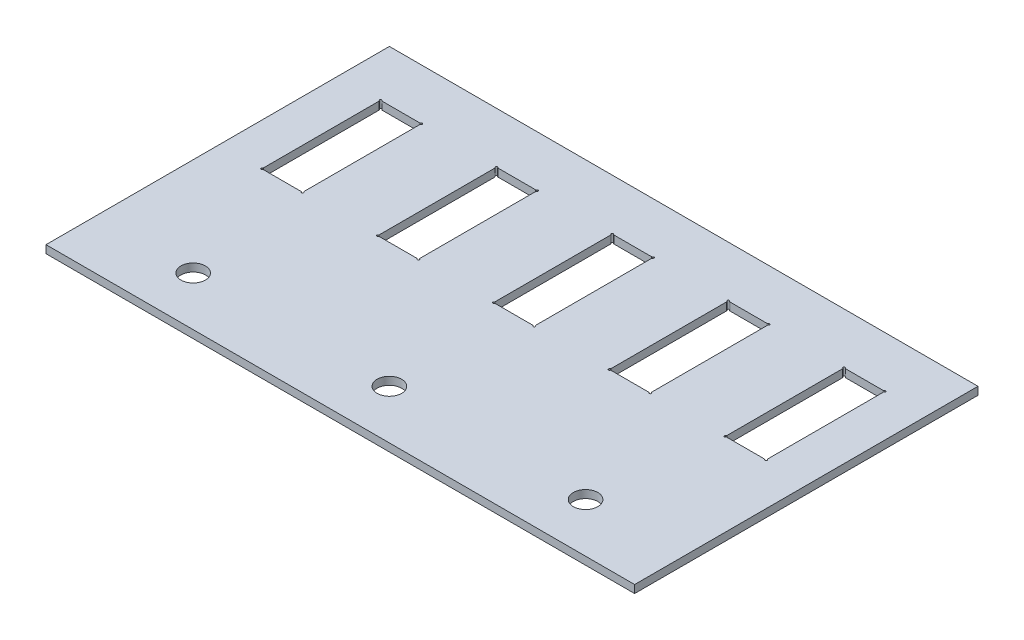
SolidWorks part; units mm, degrees
ref_plane "Front Plane" through (0, 0, 0) normal (0, 0, 1) x (1, 0, 0)
ref_plane "Top Plane" through (0, 0, 0) normal (0, 1, 0) x (1, 0, 0)
ref_plane "Right Plane" through (0, 0, 0) normal (1, 0, 0) x (0, 0, -1)
sketch "Sketch1" plane through (0, 0, 0) normal (0, 1, 0) x (1, 0, 0)
  line L0 (0, 12.7) -> (152.4, 12.7) construction
  line L1 (0, 0) -> (152.4, 0)
  line L2 (0, 0) -> (0, 88.9)
  line L3 (0, 88.9) -> (152.4, 88.9)
  line L4 (152.4, 0) -> (152.4, 88.9)
  line L5 (76.2, 88.9) -> (76.2, 0) construction
  line L6 (25.4, 0) -> (25.4, 88.9) construction
  circle A0 centre (76.2, 12.7) radius 3.175
  circle A1 centre (25.4, 12.7) radius 3.175
  circle A2 centre (127, 12.7) radius 3.175
  point P17 (18.0637, 12.7)
  dimension "D4" = 6.35
  dimension "D1" = 152.4
  dimension "D2" = 88.9
  dimension "D3" = 12.7
  dimension "D5" = 25.4
extrude "Boss-Extrude1" add sketch "Sketch1" along normal blind 2.032
sketch "Sketch2" plane through (0, 0, 0) normal (0, -1, 0) x (1, 0, 0)
  line L0 (81.4705, -75.259) -> (81.4705, -45.391)
  line L1 (71.3625, -75.692) -> (81.0375, -75.692)
  line L2 (111.4705, -75.259) -> (111.4705, -45.391)
  line L3 (101.3625, -75.692) -> (111.0375, -75.692)
  line L4 (152.4, -25.4) -> (0, -25.4) construction
  line L5 (152.4, 0) -> (152.4, -88.9) construction
  line L6 (0, -88.9) -> (0, 0) construction
  line L7 (0, 0) -> (152.4, 0) construction
  line L8 (81.0375, -44.958) -> (71.3625, -44.958)
  line L9 (111.0375, -44.958) -> (101.3625, -44.958)
  line L10 (100.9295, -45.391) -> (100.9295, -75.259)
  line L11 (70.9295, -45.391) -> (70.9295, -75.259)
  line L12 (106.2, -44.958) -> (106.2, -75.692) construction
  line L13 (111.4705, -60.325) -> (100.9295, -60.325) construction
  line L14 (141.4705, -75.259) -> (141.4705, -45.391)
  line L15 (131.3625, -75.692) -> (141.0375, -75.692)
  line L16 (141.0375, -44.958) -> (131.3625, -44.958)
  line L17 (130.9295, -45.391) -> (130.9295, -75.259)
  line L18 (136.2, -44.958) -> (136.2, -75.692) construction
  line L19 (141.4705, -60.325) -> (130.9295, -60.325) construction
  line L20 (81.4705, -75.259) -> (81.4705, -45.391)
  line L21 (71.3625, -75.692) -> (81.0375, -75.692)
  line L22 (81.0375, -44.958) -> (71.3625, -44.958)
  line L23 (70.9295, -45.391) -> (70.9295, -75.259)
  line L24 (76.2, -44.958) -> (76.2, -75.692) construction
  line L25 (81.4705, -60.325) -> (70.9295, -60.325) construction
  line L26 (111.4705, -75.259) -> (111.4705, -45.391)
  line L27 (101.3625, -75.692) -> (111.0375, -75.692)
  line L28 (111.0375, -44.958) -> (101.3625, -44.958)
  line L29 (100.9295, -45.391) -> (100.9295, -75.259)
  line L30 (106.2, -44.958) -> (106.2, -75.692) construction
  line L31 (111.4705, -60.325) -> (100.9295, -60.325) construction
  line L32 (51.4705, -75.259) -> (51.4705, -45.391)
  line L33 (41.3625, -75.692) -> (51.0375, -75.692)
  line L34 (51.0375, -44.958) -> (41.3625, -44.958)
  line L35 (40.9295, -45.391) -> (40.9295, -75.259)
  line L36 (46.2, -44.958) -> (46.2, -75.692) construction
  line L37 (51.4705, -60.325) -> (40.9295, -60.325) construction
  line L38 (81.4705, -75.259) -> (81.4705, -45.391)
  line L39 (71.3625, -75.692) -> (81.0375, -75.692)
  line L40 (81.0375, -44.958) -> (71.3625, -44.958)
  line L41 (70.9295, -45.391) -> (70.9295, -75.259)
  line L42 (76.2, -44.958) -> (76.2, -75.692) construction
  line L43 (81.4705, -60.325) -> (70.9295, -60.325) construction
  line L44 (51.4705, -75.259) -> (51.4705, -45.391)
  line L45 (41.3625, -75.692) -> (51.0375, -75.692)
  line L46 (51.0375, -44.958) -> (41.3625, -44.958)
  line L47 (40.9295, -45.391) -> (40.9295, -75.259)
  line L48 (46.2, -44.958) -> (46.2, -75.692) construction
  line L49 (51.4705, -60.325) -> (40.9295, -60.325) construction
  line L50 (21.4705, -75.259) -> (21.4705, -45.391)
  line L51 (11.3625, -75.692) -> (21.0375, -75.692)
  line L52 (21.0375, -44.958) -> (11.3625, -44.958)
  line L53 (10.9295, -45.391) -> (10.9295, -75.259)
  line L54 (16.2, -44.958) -> (16.2, -75.692) construction
  line L55 (21.4705, -60.325) -> (10.9295, -60.325) construction
  line L56 (81.4705, -75.259) -> (111.4705, -75.259) construction
  line L57 (81.4705, -75.259) -> (51.4705, -75.259) construction
  line L58 (152.4, -88.9) -> (152.4, -25.4) construction
  line L59 (152.4, -57.15) -> (0, -57.15) construction
  line L60 (76.2, -44.958) -> (76.2, -75.692) construction
  line L61 (81.4705, -60.325) -> (70.9295, -60.325) construction
  line L66 (81.4705, -44.958) -> (70.9295, -44.958)
  line L67 (81.4705, -75.692) -> (81.4705, -44.958)
  line L68 (70.9295, -75.692) -> (81.4705, -75.692)
  line L69 (70.9295, -44.958) -> (70.9295, -75.692)
  line L70 (81.4705, -44.958) -> (70.9295, -44.958) construction
  line L71 (81.4705, -75.692) -> (81.4705, -44.958) construction
  line L72 (70.9295, -75.692) -> (81.4705, -75.692) construction
  line L73 (70.9295, -44.958) -> (70.9295, -75.692) construction
  arc A0 (81.254, -75.817) -> (81.5955, -75.4755) centre (81.4705, -75.692) ccw
  arc A1 (70.8045, -75.4755) -> (71.146, -75.817) centre (70.9295, -75.692) ccw
  arc A2 (81.5955, -45.1745) -> (81.254, -44.833) centre (81.4705, -44.958) ccw
  arc A3 (71.146, -44.833) -> (70.8045, -45.1745) centre (70.9295, -44.958) ccw
  arc A4 (81.5955, -75.4755) -> (81.4705, -75.259) centre (81.7205, -75.259) cw
  arc A5 (81.254, -75.817) -> (81.0375, -75.692) centre (81.0375, -75.942) ccw
  arc A6 (71.146, -75.817) -> (71.3625, -75.692) centre (71.3625, -75.942) cw
  arc A7 (70.8045, -75.4755) -> (70.9295, -75.259) centre (70.6795, -75.259) ccw
  arc A8 (70.8045, -45.1745) -> (70.9295, -45.391) centre (70.6795, -45.391) cw
  arc A9 (71.146, -44.833) -> (71.3625, -44.958) centre (71.3625, -44.708) ccw
  arc A10 (81.5955, -45.1745) -> (81.4705, -45.391) centre (81.7205, -45.391) ccw
  arc A11 (81.254, -44.833) -> (81.0375, -44.958) centre (81.0375, -44.708) cw
  arc A12 (111.254, -75.817) -> (111.5955, -75.4755) centre (111.4705, -75.692) ccw
  arc A13 (100.8045, -75.4755) -> (101.146, -75.817) centre (100.9295, -75.692) ccw
  arc A14 (111.5955, -45.1745) -> (111.254, -44.833) centre (111.4705, -44.958) ccw
  arc A15 (101.146, -44.833) -> (100.8045, -45.1745) centre (100.9295, -44.958) ccw
  arc A16 (111.5955, -75.4755) -> (111.4705, -75.259) centre (111.7205, -75.259) cw
  arc A17 (111.254, -75.817) -> (111.0375, -75.692) centre (111.0375, -75.942) ccw
  arc A18 (101.146, -75.817) -> (101.3625, -75.692) centre (101.3625, -75.942) cw
  arc A19 (100.8045, -75.4755) -> (100.9295, -75.259) centre (100.6795, -75.259) ccw
  arc A20 (100.8045, -45.1745) -> (100.9295, -45.391) centre (100.6795, -45.391) cw
  arc A21 (101.146, -44.833) -> (101.3625, -44.958) centre (101.3625, -44.708) ccw
  arc A22 (111.5955, -45.1745) -> (111.4705, -45.391) centre (111.7205, -45.391) ccw
  arc A23 (111.254, -44.833) -> (111.0375, -44.958) centre (111.0375, -44.708) cw
  arc A24 (141.254, -75.817) -> (141.5955, -75.4755) centre (141.4705, -75.692) ccw
  arc A25 (130.8045, -75.4755) -> (131.146, -75.817) centre (130.9295, -75.692) ccw
  arc A26 (141.5955, -45.1745) -> (141.254, -44.833) centre (141.4705, -44.958) ccw
  arc A27 (131.146, -44.833) -> (130.8045, -45.1745) centre (130.9295, -44.958) ccw
  arc A28 (141.5955, -75.4755) -> (141.4705, -75.259) centre (141.7205, -75.259) cw
  arc A29 (141.254, -75.817) -> (141.0375, -75.692) centre (141.0375, -75.942) ccw
  arc A30 (131.146, -75.817) -> (131.3625, -75.692) centre (131.3625, -75.942) cw
  arc A31 (130.8045, -75.4755) -> (130.9295, -75.259) centre (130.6795, -75.259) ccw
  arc A32 (130.8045, -45.1745) -> (130.9295, -45.391) centre (130.6795, -45.391) cw
  arc A33 (131.146, -44.833) -> (131.3625, -44.958) centre (131.3625, -44.708) ccw
  arc A34 (141.5955, -45.1745) -> (141.4705, -45.391) centre (141.7205, -45.391) ccw
  arc A35 (141.254, -44.833) -> (141.0375, -44.958) centre (141.0375, -44.708) cw
  arc A36 (81.254, -75.817) -> (81.5955, -75.4755) centre (81.4705, -75.692) ccw
  arc A37 (70.8045, -75.4755) -> (71.146, -75.817) centre (70.9295, -75.692) ccw
  arc A38 (81.5955, -45.1745) -> (81.254, -44.833) centre (81.4705, -44.958) ccw
  arc A39 (71.146, -44.833) -> (70.8045, -45.1745) centre (70.9295, -44.958) ccw
  arc A40 (81.5955, -75.4755) -> (81.4705, -75.259) centre (81.7205, -75.259) cw
  arc A41 (81.254, -75.817) -> (81.0375, -75.692) centre (81.0375, -75.942) ccw
  arc A42 (71.146, -75.817) -> (71.3625, -75.692) centre (71.3625, -75.942) cw
  arc A43 (70.8045, -75.4755) -> (70.9295, -75.259) centre (70.6795, -75.259) ccw
  arc A44 (70.8045, -45.1745) -> (70.9295, -45.391) centre (70.6795, -45.391) cw
  arc A45 (71.146, -44.833) -> (71.3625, -44.958) centre (71.3625, -44.708) ccw
  arc A46 (81.5955, -45.1745) -> (81.4705, -45.391) centre (81.7205, -45.391) ccw
  arc A47 (81.254, -44.833) -> (81.0375, -44.958) centre (81.0375, -44.708) cw
  arc A48 (111.254, -75.817) -> (111.5955, -75.4755) centre (111.4705, -75.692) ccw
  arc A49 (100.8045, -75.4755) -> (101.146, -75.817) centre (100.9295, -75.692) ccw
  arc A50 (111.5955, -45.1745) -> (111.254, -44.833) centre (111.4705, -44.958) ccw
  arc A51 (101.146, -44.833) -> (100.8045, -45.1745) centre (100.9295, -44.958) ccw
  arc A52 (111.5955, -75.4755) -> (111.4705, -75.259) centre (111.7205, -75.259) cw
  arc A53 (111.254, -75.817) -> (111.0375, -75.692) centre (111.0375, -75.942) ccw
  arc A54 (101.146, -75.817) -> (101.3625, -75.692) centre (101.3625, -75.942) cw
  arc A55 (100.8045, -75.4755) -> (100.9295, -75.259) centre (100.6795, -75.259) ccw
  arc A56 (100.8045, -45.1745) -> (100.9295, -45.391) centre (100.6795, -45.391) cw
  arc A57 (101.146, -44.833) -> (101.3625, -44.958) centre (101.3625, -44.708) ccw
  arc A58 (111.5955, -45.1745) -> (111.4705, -45.391) centre (111.7205, -45.391) ccw
  arc A59 (111.254, -44.833) -> (111.0375, -44.958) centre (111.0375, -44.708) cw
  arc A60 (51.254, -75.817) -> (51.5955, -75.4755) centre (51.4705, -75.692) ccw
  arc A61 (40.8045, -75.4755) -> (41.146, -75.817) centre (40.9295, -75.692) ccw
  arc A62 (51.5955, -45.1745) -> (51.254, -44.833) centre (51.4705, -44.958) ccw
  arc A63 (41.146, -44.833) -> (40.8045, -45.1745) centre (40.9295, -44.958) ccw
  arc A64 (51.5955, -75.4755) -> (51.4705, -75.259) centre (51.7205, -75.259) cw
  arc A65 (51.254, -75.817) -> (51.0375, -75.692) centre (51.0375, -75.942) ccw
  arc A66 (41.146, -75.817) -> (41.3625, -75.692) centre (41.3625, -75.942) cw
  arc A67 (40.8045, -75.4755) -> (40.9295, -75.259) centre (40.6795, -75.259) ccw
  arc A68 (40.8045, -45.1745) -> (40.9295, -45.391) centre (40.6795, -45.391) cw
  arc A69 (41.146, -44.833) -> (41.3625, -44.958) centre (41.3625, -44.708) ccw
  arc A70 (51.5955, -45.1745) -> (51.4705, -45.391) centre (51.7205, -45.391) ccw
  arc A71 (51.254, -44.833) -> (51.0375, -44.958) centre (51.0375, -44.708) cw
  arc A72 (81.254, -75.817) -> (81.5955, -75.4755) centre (81.4705, -75.692) ccw
  arc A73 (70.8045, -75.4755) -> (71.146, -75.817) centre (70.9295, -75.692) ccw
  arc A74 (81.5955, -45.1745) -> (81.254, -44.833) centre (81.4705, -44.958) ccw
  arc A75 (71.146, -44.833) -> (70.8045, -45.1745) centre (70.9295, -44.958) ccw
  arc A76 (81.5955, -75.4755) -> (81.4705, -75.259) centre (81.7205, -75.259) cw
  arc A77 (81.254, -75.817) -> (81.0375, -75.692) centre (81.0375, -75.942) ccw
  arc A78 (71.146, -75.817) -> (71.3625, -75.692) centre (71.3625, -75.942) cw
  arc A79 (70.8045, -75.4755) -> (70.9295, -75.259) centre (70.6795, -75.259) ccw
  arc A80 (70.8045, -45.1745) -> (70.9295, -45.391) centre (70.6795, -45.391) cw
  arc A81 (71.146, -44.833) -> (71.3625, -44.958) centre (71.3625, -44.708) ccw
  arc A82 (81.5955, -45.1745) -> (81.4705, -45.391) centre (81.7205, -45.391) ccw
  arc A83 (81.254, -44.833) -> (81.0375, -44.958) centre (81.0375, -44.708) cw
  arc A84 (51.254, -75.817) -> (51.5955, -75.4755) centre (51.4705, -75.692) ccw
  arc A85 (40.8045, -75.4755) -> (41.146, -75.817) centre (40.9295, -75.692) ccw
  arc A86 (51.5955, -45.1745) -> (51.254, -44.833) centre (51.4705, -44.958) ccw
  arc A87 (41.146, -44.833) -> (40.8045, -45.1745) centre (40.9295, -44.958) ccw
  arc A88 (51.5955, -75.4755) -> (51.4705, -75.259) centre (51.7205, -75.259) cw
  arc A89 (51.254, -75.817) -> (51.0375, -75.692) centre (51.0375, -75.942) ccw
  arc A90 (41.146, -75.817) -> (41.3625, -75.692) centre (41.3625, -75.942) cw
  arc A91 (40.8045, -75.4755) -> (40.9295, -75.259) centre (40.6795, -75.259) ccw
  arc A92 (40.8045, -45.1745) -> (40.9295, -45.391) centre (40.6795, -45.391) cw
  arc A93 (41.146, -44.833) -> (41.3625, -44.958) centre (41.3625, -44.708) ccw
  arc A94 (51.5955, -45.1745) -> (51.4705, -45.391) centre (51.7205, -45.391) ccw
  arc A95 (51.254, -44.833) -> (51.0375, -44.958) centre (51.0375, -44.708) cw
  arc A96 (21.254, -75.817) -> (21.5955, -75.4755) centre (21.4705, -75.692) ccw
  arc A97 (10.8045, -75.4755) -> (11.146, -75.817) centre (10.9295, -75.692) ccw
  arc A98 (21.5955, -45.1745) -> (21.254, -44.833) centre (21.4705, -44.958) ccw
  arc A99 (11.146, -44.833) -> (10.8045, -45.1745) centre (10.9295, -44.958) ccw
  arc A100 (21.5955, -75.4755) -> (21.4705, -75.259) centre (21.7205, -75.259) cw
  arc A101 (21.254, -75.817) -> (21.0375, -75.692) centre (21.0375, -75.942) ccw
  arc A102 (11.146, -75.817) -> (11.3625, -75.692) centre (11.3625, -75.942) cw
  arc A103 (10.8045, -75.4755) -> (10.9295, -75.259) centre (10.6795, -75.259) ccw
  arc A104 (10.8045, -45.1745) -> (10.9295, -45.391) centre (10.6795, -45.391) cw
  arc A105 (11.146, -44.833) -> (11.3625, -44.958) centre (11.3625, -44.708) ccw
  arc A106 (21.5955, -45.1745) -> (21.4705, -45.391) centre (21.7205, -45.391) ccw
  arc A107 (21.254, -44.833) -> (21.0375, -44.958) centre (21.0375, -44.708) cw
  dimension "D6" = 0.5
  dimension "D4" = 30
  dimension "D5" = 30
  dimension "D1" = 25.4
  dimension "D7" = 0
  dimension "D2" = 3
  dimension "D3" = 3
extrude "Cut-Extrude1" cut sketch "Sketch2" against normal through all contours A26 A35 L16 A33 A27 A32 L17 A31 A25 A30 L15 A29 A24 A28 L14 A34 | A14 A23 L9 A21 A15 A20 L10 A19 A13 A18 L3 A17 A12 A16 L2 A22 | A2 A11 L8 A9 A3 A8 L11 A7 A1 A6 L1 A5 A0 A4 L0 A10 | A62 A71 L34 A69 A63 A68 L35 A67 A61 A66 L33 A65 A60 A64 L32 A70 | A98 A107 L52 A105 A99 A104 L53 A103 A97 A102 L51 A101 A96 A100 L50 A106
sketch "Sketch3" plane through (0, 0, 0) normal (0, -1, 0) x (1, 0, 0)
  line L0 (152.4, -31.75) -> (0, -31.75) construction
  line L1 (152.4, 0) -> (152.4, -88.9) construction
  line L2 (0, -88.9) -> (0, 0) construction
  line L3 (0, 0) -> (152.4, 0) construction
  line L4 (152.4, -60.325) -> (0, -60.325) construction
  line L5 (0, -31.75) -> (152.4, -31.75) construction
  line L6 (0, -31.75) -> (0, -88.9) construction
  line L7 (0, -88.9) -> (152.4, -88.9) construction
  line L8 (152.4, -31.75) -> (152.4, -88.9) construction
  dimension "D1" = 31.75
equation "\"D5@Sketch2\"=\"D4@Sketch2\""
